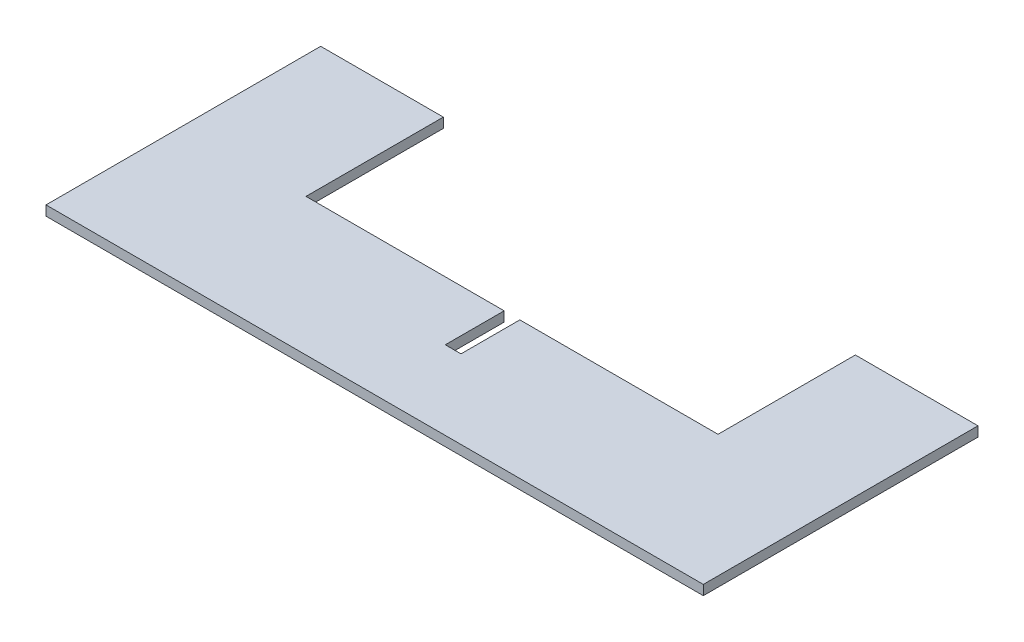
SolidWorks part; units mm, degrees
ref_plane "Alzado" through (0, 0, 0) normal (0, 0, 1) x (1, 0, 0)
ref_plane "Planta" through (0, 0, 0) normal (0, 1, 0) x (1, 0, 0)
ref_plane "Vista lateral" through (0, 0, 0) normal (1, 0, 0) x (0, 0, -1)
sketch "Croquis1" plane through (0, 0, 0) normal (0, 1, 0) x (1, 0, 0)
  line L0 (0, 0) -> (33.5, 0)
  line L1 (33.5, 0) -> (33.5, 14)
  line L2 (33.5, 14) -> (27.25, 14)
  line L3 (27.25, 14) -> (27.25, 7)
  line L4 (27.25, 7) -> (17.15, 7)
  line L5 (17.15, 7) -> (17.15, 4)
  line L6 (17.15, 4) -> (16.35, 4)
  line L7 (16.35, 4) -> (16.35, 7)
  line L8 (16.35, 7) -> (6.25, 7)
  line L9 (6.25, 7) -> (6.25, 14)
  line L10 (6.25, 14) -> (0, 14)
  line L11 (0, 14) -> (0, 0)
  line L12 (16.75, 4) -> (16.75, 0) construction
  point P14 (16.3113, 3.3547)
  dimension "D1" = 14
  dimension "D2" = 7
  dimension "D3" = 0.8
  dimension "D4" = 4
  dimension "D5" = 21
  dimension "D6" = 33.5
extrude "Saliente-Extruir1" add sketch "Croquis1" along normal blind 0.5
